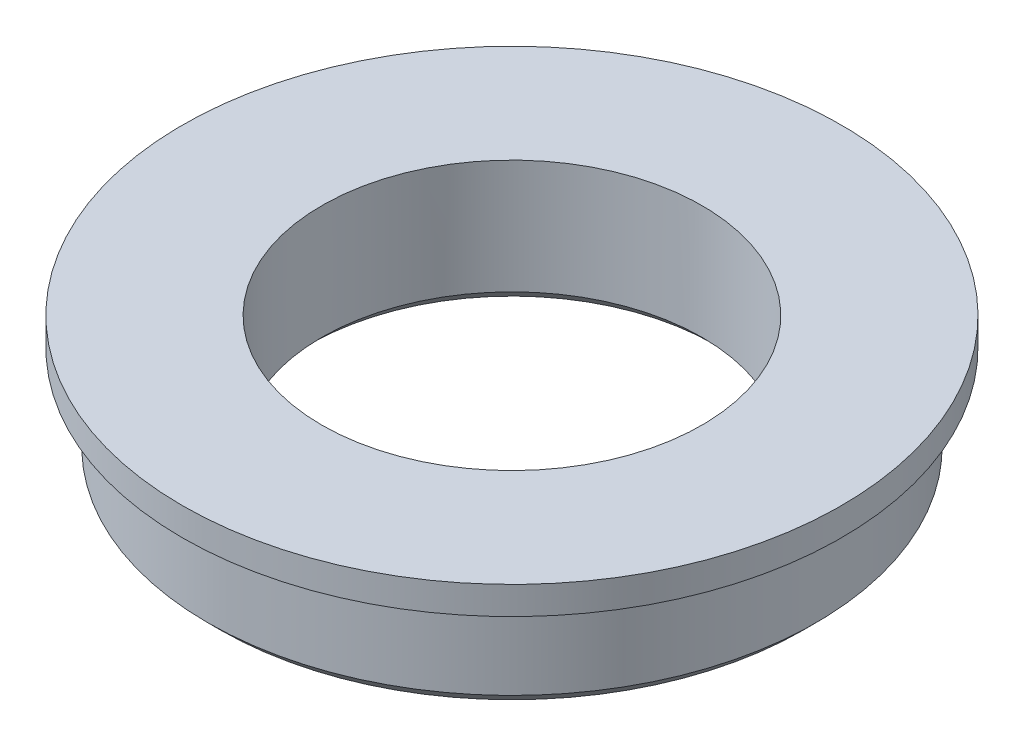
SolidWorks part; units mm, degrees
material "合金钢"
ref_plane "前视基准面" through (0, 0, 0) normal (0, 0, 1) x (1, 0, 0)
ref_plane "上视基准面" through (0, 0, 0) normal (0, 1, 0) x (1, 0, 0)
ref_plane "右视基准面" through (0, 0, 0) normal (1, 0, 0) x (0, 0, -1)
sketch "草图1" plane through (0, 0, 0) normal (0, 0, 1) x (1, 0, 0)
  line L0 (0, 22.0883) -> (0, -24.9115) construction
  line L1 (-25.4863, 0) -> (28.0892, 0) construction
  line L2 (-7.5, 0) -> (-12, 0)
  line L3 (-12, 0) -> (-12, 3.9)
  line L4 (-12, 3.9) -> (-13, 3.9)
  line L5 (-13, 3.9) -> (-13, 5)
  line L6 (-13, 5) -> (-7.5, 5)
  line L7 (-7.5, 5) -> (-7.5, 0)
  dimension "D1" = 15
  dimension "D2" = 24
  dimension "D3" = 5
  dimension "D4" = 13
  dimension "D5" = 1.1
revolve "旋转1" add sketch "草图1" angle 360 about L0
chamfer "倒角1" distance 0.5 angle 45 2 edges at (0, 0, 7.5) (0, 0, 12)
